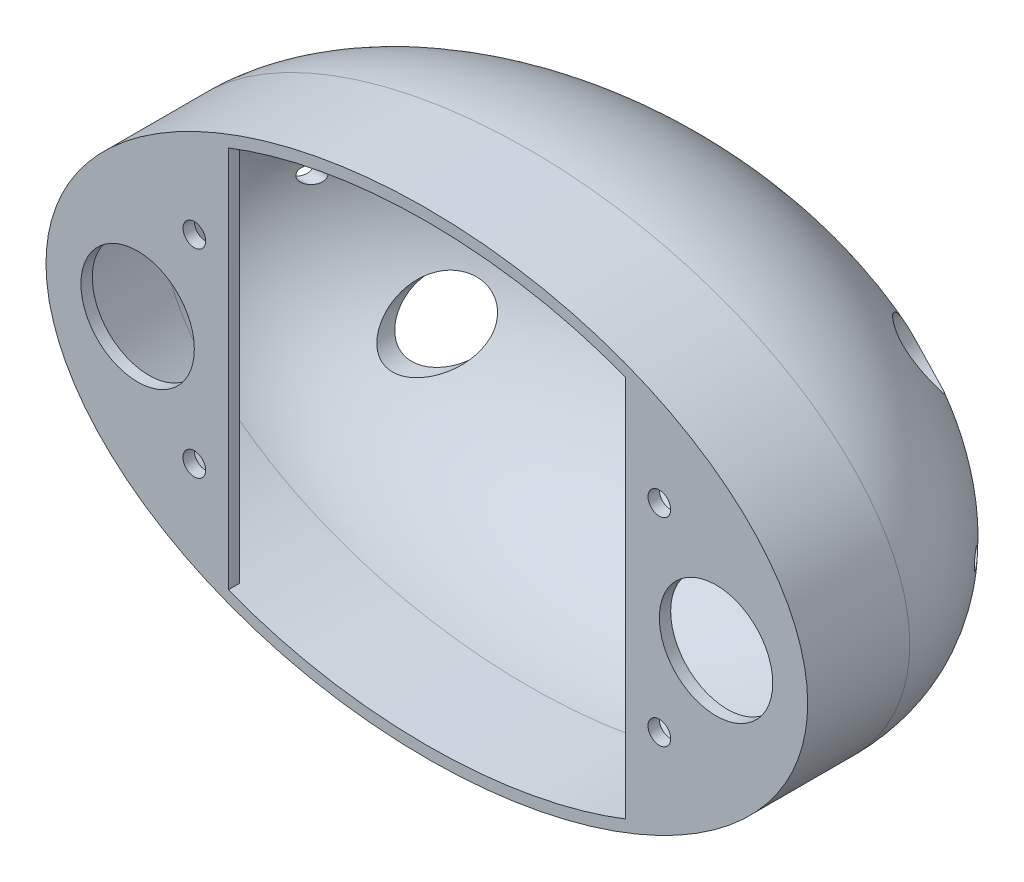
SolidWorks part; units mm, degrees
ref_plane "前视基准面" through (0, 0, 0) normal (0, 0, 1) x (1, 0, 0)
ref_plane "上视基准面" through (0, 0, 0) normal (0, 1, 0) x (1, 0, 0)
ref_plane "右视基准面" through (0, 0, 0) normal (1, 0, 0) x (0, 0, -1)
sketch "草图1" plane through (0, 0, 0) normal (0, 0, 1) x (1, 0, 0)
  line L0 (0, 38.817) -> (0, -48.8884) construction
  line L1 (0, -30) -> (47, -30) construction
  line L2 (47, -30) -> (47, 0) construction
  line L3 (-67.1568, 0) -> (-65.1568, 0)
  line L4 (65.1568, 0) -> (67.1568, 0)
  ellipse E0 centre (0, 0) end of major axis (67.1568, 0) minor radius 42 (-67.1568, 0) -> (67.1568, 0) ccw
  ellipse E1 centre (0, 0) end of major axis (65.1568, 0) minor radius 40 (-65.1568, 0) -> (65.1568, 0) ccw
  dimension "D1" = 30
  dimension "D2" = 47
  dimension "D3" = 2
  dimension "D4" = 2
  dimension "D5" = 84
revolve "旋转2" add sketch "草图1" angle 180 about L3
sketch "草图3" plane through (0, 0, 0) normal (0, 0, 1) x (1, 0, 0)
  ellipse E0 centre (0, 0) end of major axis (67.1568, 0) minor radius 42
  ellipse E1 centre (0, 0) end of major axis (67.1568, 0) minor radius 42 (67.1568, 0) -> (-67.1568, 0) ccw construction
  ellipse E2 centre (0, 0) end of major axis (65.1568, 0) minor radius 40
  ellipse E3 centre (0, 0) end of major axis (65.1568, 0) minor radius 40 (65.1568, 0) -> (-65.1568, 0) ccw construction
  ellipse E4 centre (0, 0) end of major axis (67.1568, 0) minor radius 42 (-67.1568, 0) -> (67.1568, 0) ccw construction
  point P1 (67.1568, 0)
  point P20 (65.1568, 0)
  point P28 (0, 40)
  point P29 (-67.1568, 0)
  point P30 (0, -42)
extrude "凸台-拉伸1" add sketch "草图3" along normal blind 18
sketch "草图4" plane through (0, 0, 18) normal (0, 0, 1) x (1, 0, 0)
  line L0 (-35, 33.7391) -> (-35, -33.7391)
  line L1 (0, 0) -> (0, 52.9966) construction
  line L2 (35, 33.7391) -> (35, -33.7391)
  ellipse E0 centre (0, 0) end of major axis (-65.1568, 0) minor radius 40 (35, 33.7391) -> (35, -33.7391) cw
  ellipse E2 centre (0, 0) end of major axis (65.1568, 0) minor radius 40 (-35, 33.7391) -> (-35, -33.7391) ccw
  ellipse E3 centre (0, 0) end of major axis (65.1568, 0) minor radius 40 (-65.1568, 0) -> (65.1568, 0) ccw construction
  ellipse E4 centre (0, 0) end of major axis (65.1568, 0) minor radius 40 construction
  point P2 (-65.1568, 0)
  dimension "D1" = 70
extrude "凸台-拉伸2" add sketch "草图4" against normal blind 2
sketch "草图5" plane through (0, 0, 18) normal (0, 0, 1) x (1, 0, 0)
  line L0 (-35, 0) -> (85.9493, 0) construction
  line L1 (-35, -33.7391) -> (-35, 33.7391) construction
  line L2 (0, 0) -> (0, 60.0848) construction
  line L3 (35, 33.7391) -> (35, -33.7391) construction
  circle A0 centre (41, 17.5) radius 2
  circle A1 centre (41, -17.5) radius 2
  circle A2 centre (-41, -17.5) radius 2
  circle A3 centre (-41, 17.5) radius 2
  circle A4 centre (51, 0) radius 10
  circle A5 centre (-51, 0) radius 10
  dimension "D1" = 4
  dimension "D2" = 35
  dimension "D3" = 82
  dimension "D4" = 20
  dimension "D5" = 16
extrude "切除-拉伸2" cut sketch "草图5" against normal up to next
sketch "草图6" plane through (0, 0, 18) normal (0, 0, 1) x (1, 0, 0)
  line L0 (0, 0) -> (0, 62.5023) construction
  line L1 (0, 0) -> (103.5503, 0) construction
  circle A0 centre (41, -17.5) radius 6
  circle A1 centre (41, 17.5) radius 6
  circle A2 centre (-41, 17.5) radius 6
  circle A3 centre (-41, -17.5) radius 6
  dimension "D1" = 12
extrude "切除-拉伸3" cut sketch "草图6" against normal through all from offset 10 offset against normal yes
sketch "草图7" plane through (0, 0, 0) normal (1, 0, 0) x (0, 0, -1)
  line L0 (0, 0) -> (47.3247, 0) construction
  line L1 (0, -42) -> (0, 0) construction
  circle A0 centre (19, 0) radius 1.5
  circle A1 centre (29, 0) radius 1.5
  dimension "D1" = 3
  dimension "D2" = 3
  dimension "D3" = 10
  dimension "D4" = 19
extrude "切除-拉伸4" cut sketch "草图7" against normal through all and the other way through all
